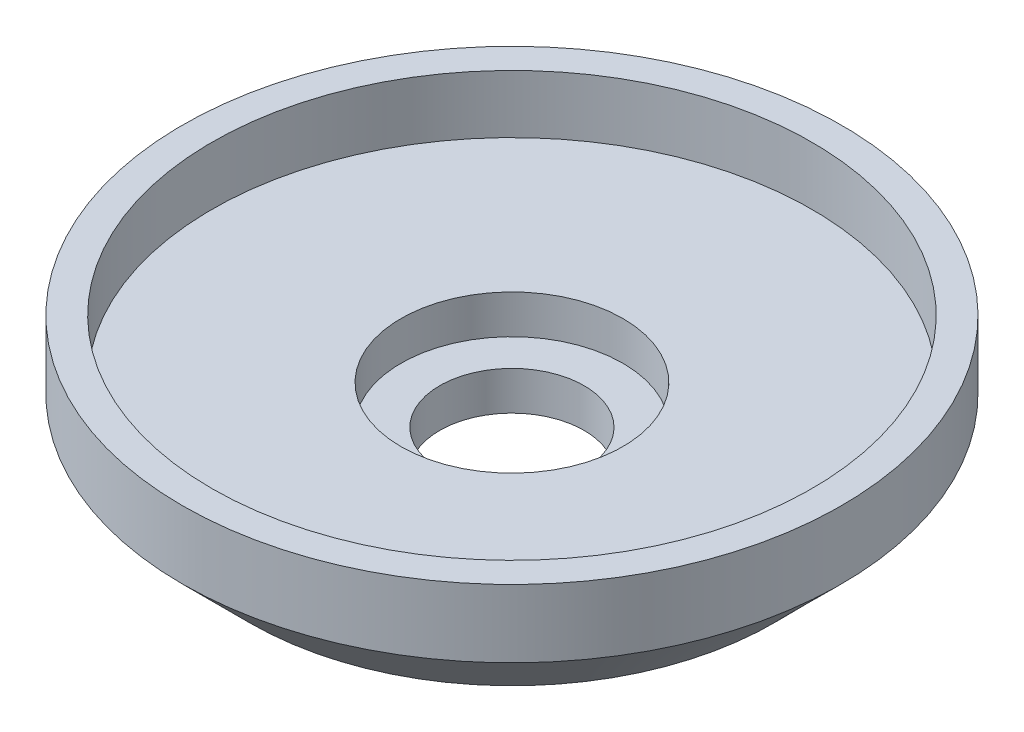
SolidWorks part; units mm, degrees
material "ABS"
ref_plane "Front Plane" through (0, 0, 0) normal (0, 0, 1) x (1, 0, 0)
ref_plane "Top Plane" through (0, 0, 0) normal (0, 1, 0) x (1, 0, 0)
ref_plane "Right Plane" through (0, 0, 0) normal (1, 0, 0) x (0, 0, -1)
sketch "Sketch1" plane through (0, 0, 0) normal (0, 1, 0) x (1, 0, 0)
  circle A1 centre (0, 0) radius 34
  dimension "D2" = 68
extrude "Boss-Extrude1" add sketch "Sketch1" along normal blind 14
sketch "Sketch2" plane through (0, 14, 0) normal (0, 1, 0) x (1, 0, 0)
  circle A0 centre (0, 0) radius 30.95
  dimension "D1" = 61.9
extrude "Cut-Extrude1" cut sketch "Sketch2" against normal blind 6
sketch "Sketch3" plane through (0, 8, 0) normal (0, 1, 0) x (1, 0, 0)
  circle A0 centre (0, 0) radius 11.45
  dimension "D1" = 22.9
extrude "Cut-Extrude2" cut sketch "Sketch3" against normal blind 4
sketch "Sketch4" plane through (0, 4, 0) normal (0, 1, 0) x (1, 0, 0)
  circle A0 centre (0, 0) radius 7.45
  dimension "D1" = 14.9
extrude "Cut-Extrude3" cut sketch "Sketch4" against normal blind 4
chamfer "Chamfer1" distance 7 angle 45 1 edges at (0, 0, 34)
